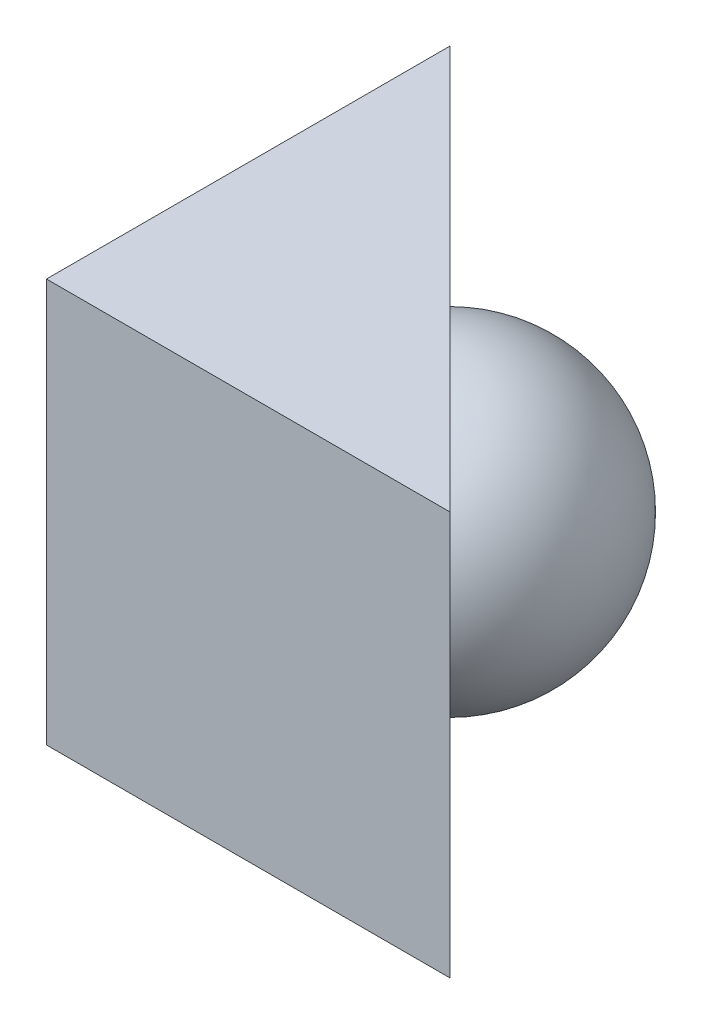
SolidWorks part; units mm, degrees
ref_plane "Front Plane" through (0, 0, 0) normal (0, 0, 1) x (1, 0, 0)
ref_plane "Top Plane" through (0, 0, 0) normal (0, 1, 0) x (1, 0, 0)
ref_plane "Right Plane" through (0, 0, 0) normal (1, 0, 0) x (0, 0, -1)
sketch "Sketch2" plane through (0, 0, 0) normal (0, 1, 0) x (1, 0, 0)
  line L0 (-18, 0) -> (18, 0)
  arc A0 (-18, 0) -> (18, 0) centre (0, 0) cw
  dimension "D1" = 18
revolve "Revolve1" add sketch "Sketch2" angle 360 about L0
sketch "Sketch3" plane through (0, 0, 0) normal (0, 1, 0) x (1, 0, 0)
  line L3 (25, -25) -> (-25, 25)
  line L6 (25, -25) -> (-25, -25)
  line L7 (-25, 25) -> (-25, -25)
  dimension "D1" = 50
  dimension "D2" = 50
extrude "Boss-Extrude1" add sketch "Sketch3" along normal mid plane 50
